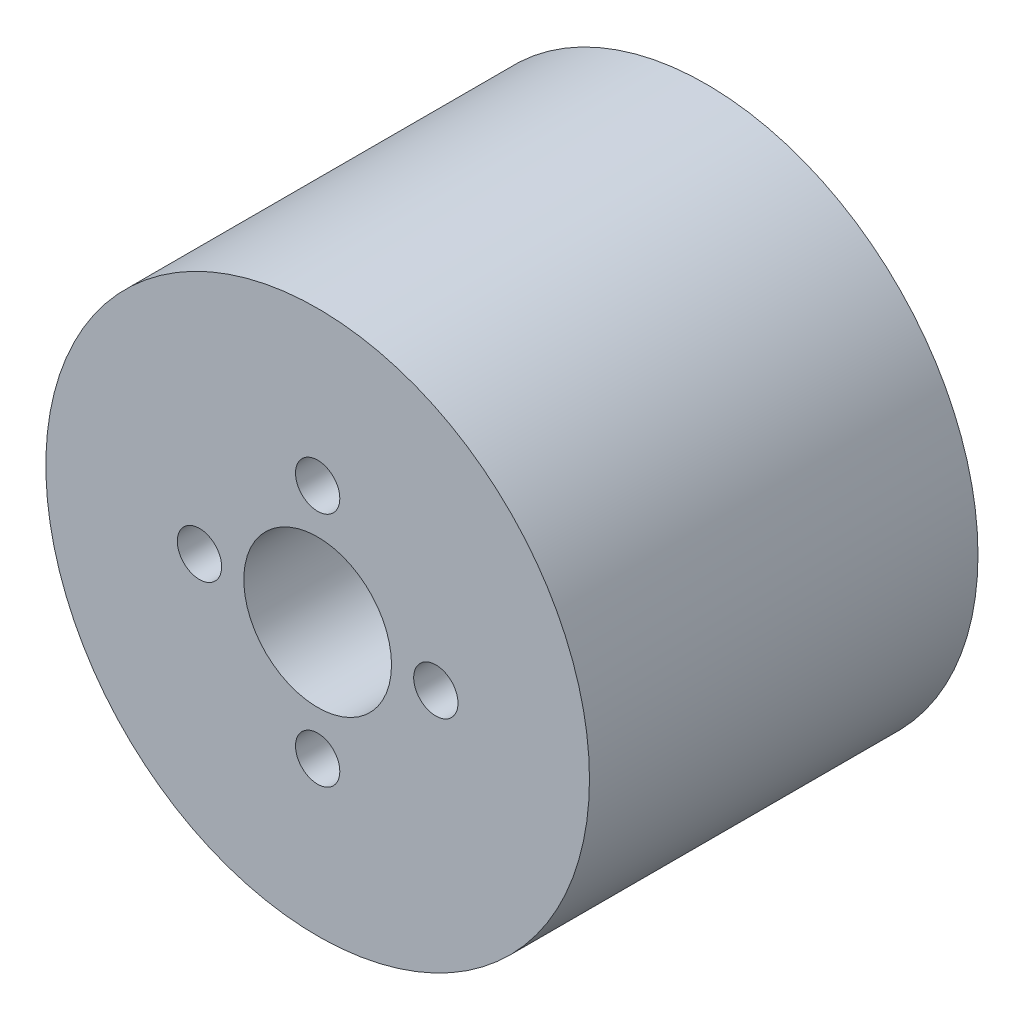
SolidWorks part; units mm, degrees
ref_plane "Alzado" through (0, 0, 0) normal (0, 0, 1) x (1, 0, 0)
ref_plane "Planta" through (0, 0, 0) normal (0, 1, 0) x (1, 0, 0)
ref_plane "Vista lateral" through (0, 0, 0) normal (1, 0, 0) x (0, 0, -1)
sketch "Croquis1" plane through (0, 0, 0) normal (0, 0, 1) x (1, 0, 0)
  circle A0 centre (0, 0) radius 18.4
  dimension "D1" = 36.8
extrude "Saliente-Extruir1" add sketch "Croquis1" along normal blind 26.3
sketch "Croquis2" plane through (0, 0, 26.3) normal (0, 0, 1) x (1, 0, 0)
  circle A0 centre (0, 8) radius 1.5
  circle A1 centre (0, 0) radius 18.4 construction
  circle A2 centre (8, 0) radius 1.5
  circle A3 centre (0, -8) radius 1.5
  circle A4 centre (-8, 0) radius 1.5
  point P13 (0, 0)
  dimension "D1" = 8
  dimension "D2" = 3
  dimension "D3" = 4
extrude "Cortar-Extruir1" cut sketch "Croquis2" against normal blind 3
sketch "Croquis3" plane through (0, 0, 26.3) normal (0, 0, 1) x (1, 0, 0)
  circle A0 centre (0, 0) radius 5
extrude "Cortar-Extruir2" cut sketch "Croquis3" against normal blind 44
sketch "Croquis4" plane through (0, 0, 0) normal (0, 0, -1) x (-1, 0, 0)
  circle A0 centre (0, 8) radius 1.5
  circle A1 centre (8, 0) radius 1.5
  circle A2 centre (0, -8) radius 1.5
  circle A3 centre (-8, 0) radius 1.5
  point P12 (0, 0)
  dimension "D1" = 8
  dimension "D2" = 4
extrude "Cortar-Extruir3" cut sketch "Croquis4" against normal blind 3
